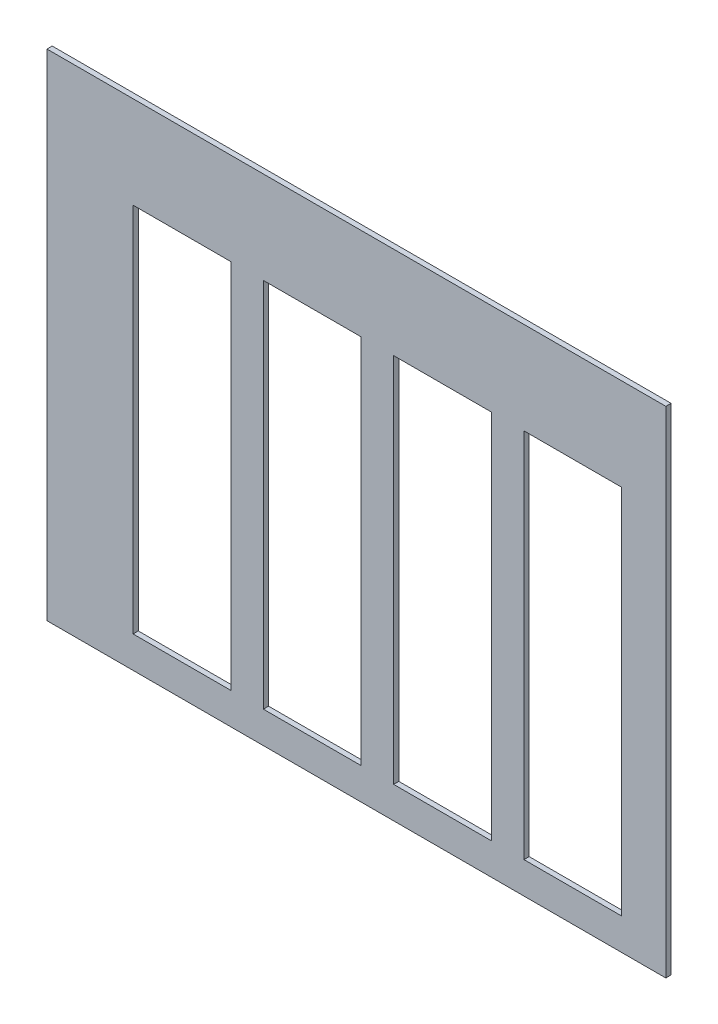
SolidWorks part; units mm, degrees
ref_plane "Front Plane" through (0, 0, 0) normal (0, 0, 1) x (1, 0, 0)
ref_plane "Top Plane" through (0, 0, 0) normal (0, 1, 0) x (1, 0, 0)
ref_plane "Right Plane" through (0, 0, 0) normal (1, 0, 0) x (0, 0, -1)
sketch "Sketch1" plane through (0, 0, 0) normal (0, 0, 1) x (1, 0, 0)
  line L0 (-242.8174, 76.7161) -> (-242.8174, -493.2839)
  line L1 (-725, 218.2229) -> (225, 218.2229)
  line L2 (-725, 218.2229) -> (-725, -541.7771)
  line L3 (-725, -541.7771) -> (225, -541.7771)
  line L4 (225, 218.2229) -> (225, -541.7771)
  line L5 (-592.8174, 76.7161) -> (-442.8174, 76.7161)
  line L6 (-592.8174, 76.7161) -> (-592.8174, -493.2839)
  line L7 (-592.8174, -493.2839) -> (-442.8174, -493.2839)
  line L8 (-442.8174, 76.7161) -> (-442.8174, -493.2839)
  line L9 (-392.8174, 76.7161) -> (-392.8174, -493.2839)
  line L10 (-392.8174, 76.7161) -> (-242.8174, 76.7161)
  line L11 (-392.8174, -493.2839) -> (-242.8174, -493.2839)
  line L12 (-42.8174, 76.7161) -> (-42.8174, -493.2839)
  line L13 (-192.8174, 76.7161) -> (-192.8174, -493.2839)
  line L14 (-192.8174, 76.7161) -> (-42.8174, 76.7161)
  line L15 (-192.8174, -493.2839) -> (-42.8174, -493.2839)
  line L16 (157.1826, 76.7161) -> (157.1826, -493.2839)
  line L17 (7.1826, 76.7161) -> (7.1826, -493.2839)
  line L18 (7.1826, 76.7161) -> (157.1826, 76.7161)
  line L19 (7.1826, -493.2839) -> (157.1826, -493.2839)
  dimension "D3" = 150
  dimension "D4" = 570
  dimension "D5" = 4
  dimension "D1" = 950
  dimension "D2" = 760
extrude "Boss-Extrude1" add sketch "Sketch1" along normal blind 8
